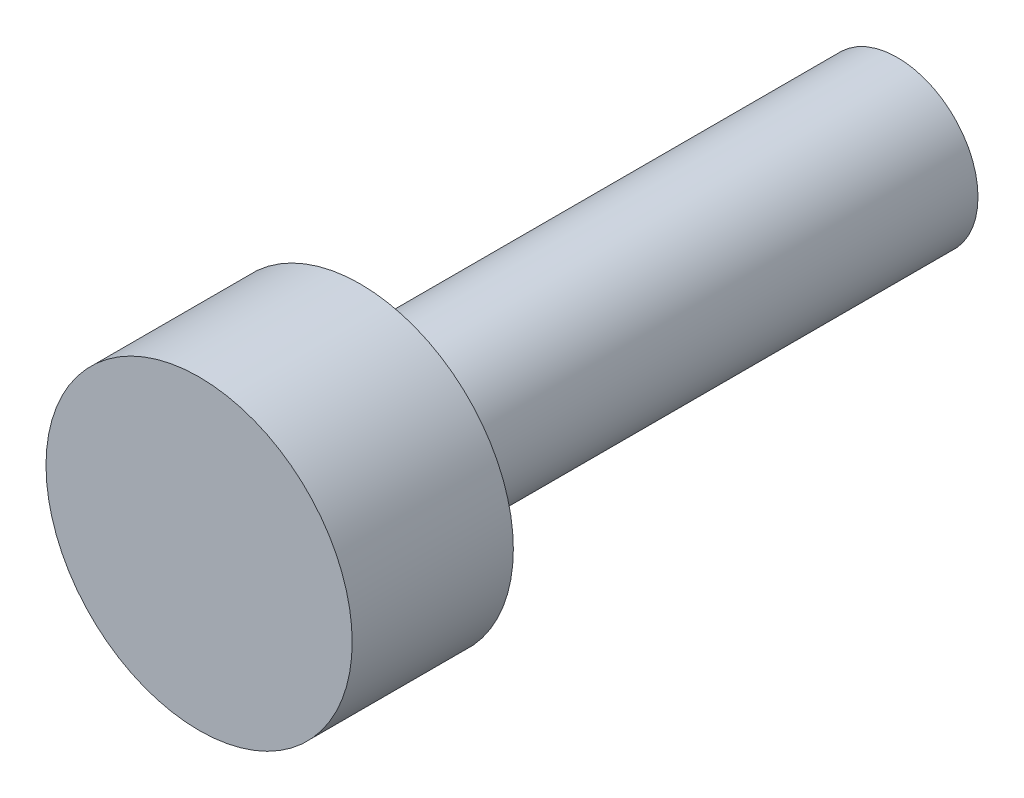
SolidWorks part; units mm, degrees
ref_plane "Front Plane" through (0, 0, 0) normal (0, 0, 1) x (1, 0, 0)
ref_plane "Top Plane" through (0, 0, 0) normal (0, 1, 0) x (1, 0, 0)
ref_plane "Right Plane" through (0, 0, 0) normal (1, 0, 0) x (0, 0, -1)
sketch "Sketch1" plane through (0, 0, 0) normal (0, 0, 1) x (1, 0, 0)
  circle A0 centre (0, 0) radius 1.5
  dimension "D1" = 3
extrude "Boss-Extrude1" add sketch "Sketch1" along normal blind 10
sketch "Sketch2" plane through (0, 0, 10) normal (0, 0, 1) x (1, 0, 0)
  circle A0 centre (0, 0) radius 2.85
  dimension "D1" = 5.7
extrude "Boss-Extrude2" add sketch "Sketch2" along normal blind 3
